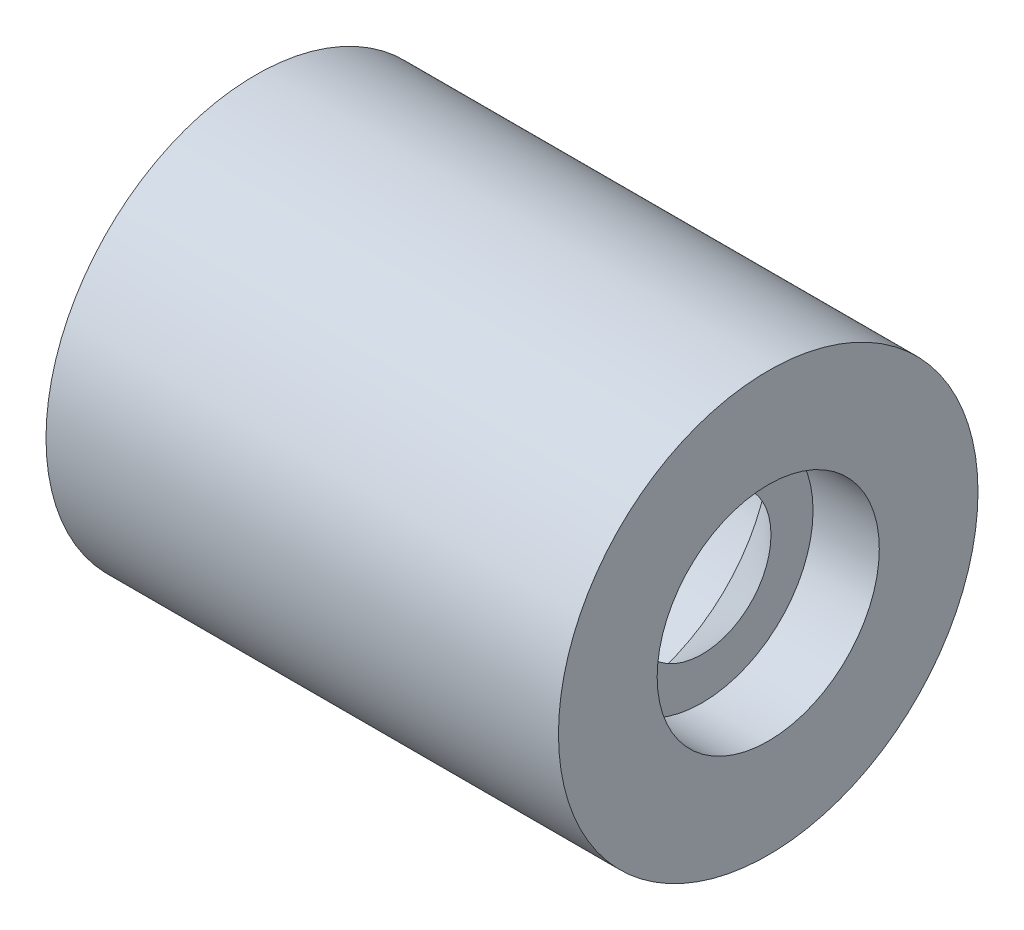
SolidWorks part; units mm, degrees
ref_plane "Front Plane" through (0, 0, 0) normal (0, 0, 1) x (1, 0, 0)
ref_plane "Top Plane" through (0, 0, 0) normal (0, 1, 0) x (1, 0, 0)
ref_plane "Right Plane" through (0, 0, 0) normal (1, 0, 0) x (0, 0, -1)
sketch "Sketch3" plane through (0, 0, 0) normal (0, 0, 1) x (1, 0, 0)
  line L0 (1.7986, 24.13) -> (-57.15, 24.13)
  line L2 (-57.15, 24.13) -> (-57.15, 17.78)
  line L3 (-57.15, 17.78) -> (-15.6639, 17.78)
  line L4 (-15.6639, 17.78) -> (-5.8214, 7.9375)
  line L5 (-5.8214, 7.9375) -> (-5.8214, -7.9375) construction
  line L6 (-5.8214, 12.7) -> (-5.8214, -12.7) construction
  line L7 (-5.8214, 7.9375) -> (-5.8214, 12.7762)
  line L8 (-5.8214, 12.7762) -> (1.7986, 12.7762)
  line L9 (1.7986, 24.1554) -> (1.7986, -24.1554) construction
  line L10 (1.7986, 12.7762) -> (1.7986, 24.13)
  line L11 (24.1721, 0) -> (-63.4646, 0) construction
  point P2 (-5.8214, 7.9375)
  point P17 (-5.8214, 8.3406)
  point P18 (-5.8214, 7.9375)
  point P20 (-63.4646, 0)
  dimension "D1" = 45
  dimension "D2" = 25.5524
  dimension "D3" = 6.35
  dimension "D4" = 48.26
  dimension "D5" = 15.875
  dimension "D6" = 57.15
revolve "Revolve1" add sketch "Sketch3" angle 360 about L11
